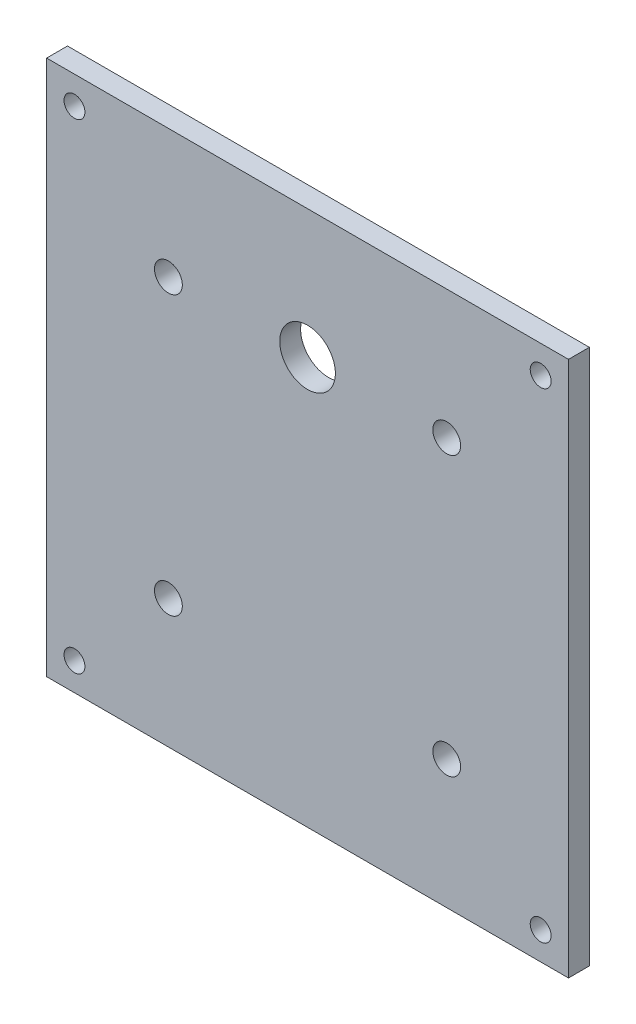
SolidWorks part; units mm, degrees
ref_plane "前视基准面" through (0, 0, 0) normal (0, 0, 1) x (1, 0, 0)
ref_plane "上视基准面" through (0, 0, 0) normal (0, 1, 0) x (1, 0, 0)
ref_plane "右视基准面" through (0, 0, 0) normal (1, 0, 0) x (0, 0, -1)
sketch "草图1" plane through (0, 0, 0) normal (0, 0, 1) x (1, 0, 0)
  line L0 (-59.1532, 21.6171) -> (7.8468, 21.6171) construction
  line L1 (7.8468, 21.6171) -> (7.8468, -47.3829) construction
  line L2 (7.8468, -47.3829) -> (-59.1532, -47.3829) construction
  line L3 (-59.1532, -47.3829) -> (-59.1532, 21.6171) construction
  line L4 (-63.1532, 25.6171) -> (11.8468, 25.6171)
  line L5 (11.8468, 25.6171) -> (11.8468, -51.3829)
  line L6 (11.8468, -51.3829) -> (-63.1532, -51.3829)
  line L7 (-63.1532, -51.3829) -> (-63.1532, 25.6171)
  line L8 (-25.6532, 21.6171) -> (-25.6532, -47.3829) construction
  line L9 (-25.6532, -12.8829) -> (-5.6532, -12.8829) construction
  line L10 (-5.6532, -12.8829) -> (-5.6532, -32.8829) construction
  line L11 (-45.6532, 7.1171) -> (-5.6532, 7.1171) construction
  circle A0 centre (-59.1532, 21.6171) radius 1.5
  circle A1 centre (7.8468, 21.6171) radius 1.5
  circle A2 centre (-59.1532, -47.3829) radius 1.5
  circle A3 centre (7.8468, -47.3829) radius 1.5
  circle A4 centre (-5.6532, -32.8829) radius 2
  circle A8 centre (-45.6532, -32.8829) radius 2
  circle A9 centre (-45.6532, 7.1171) radius 2
  circle A10 centre (-5.6532, 7.1171) radius 2
  circle A11 centre (-25.6532, 7.1171) radius 4
  dimension "D3" = 4
  dimension "D1" = 67
  dimension "D2" = 69
extrude "凸台-拉伸1" add sketch "草图1" along normal blind 3
